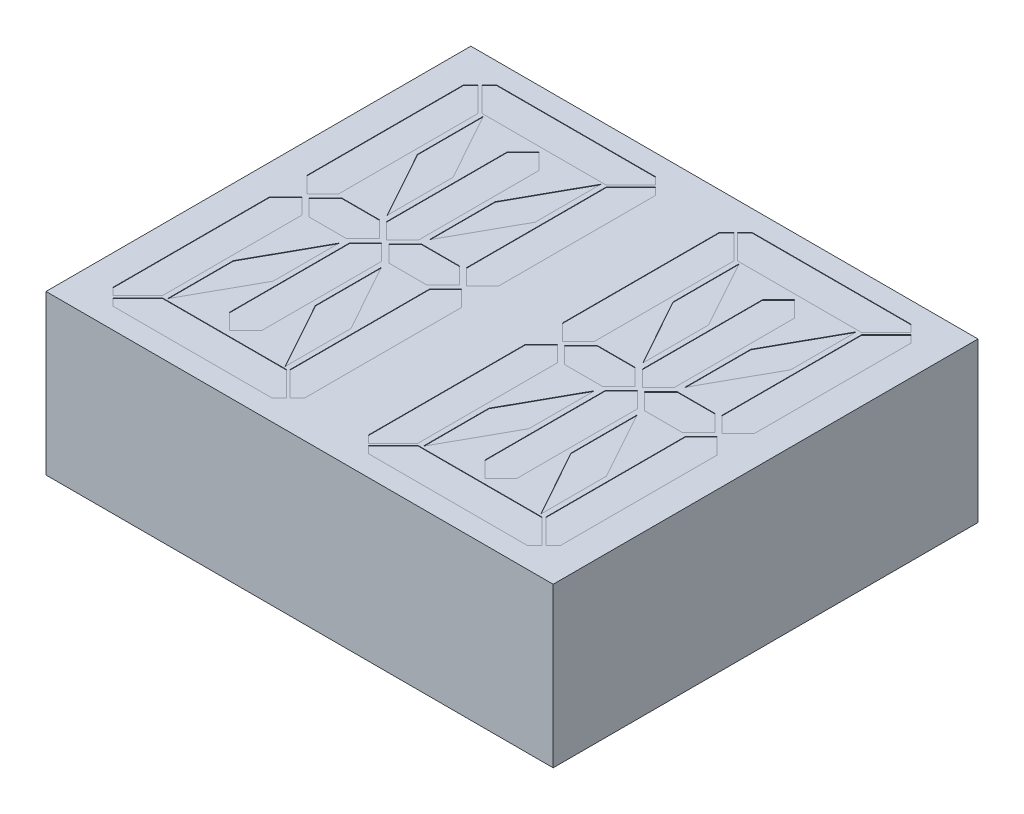
SolidWorks part; units mm, degrees
ref_plane "Front Plane" through (0, 0, 0) normal (0, 0, 1) x (1, 0, 0)
ref_plane "Top Plane" through (0, 0, 0) normal (0, 1, 0) x (1, 0, 0)
ref_plane "Right Plane" through (0, 0, 0) normal (1, 0, 0) x (0, 0, -1)
sketch "Sketch1" plane through (0, 0, 0) normal (0, 1, 0) x (1, 0, 0)
  line L1 (-12.5984, 10.5537) -> (12.5984, 10.5537)
  line L2 (-12.5984, 10.5537) -> (-12.5984, -10.5537)
  line L3 (-12.5984, -10.5537) -> (12.5984, -10.5537)
  line L4 (12.5984, 10.5537) -> (12.5984, -10.5537)
  line L5 (-12.5984, 10.5537) -> (12.5984, -10.5537) construction
  line L6 (-12.5984, -10.5537) -> (12.5984, 10.5537) construction
  point P0 (0, 0)
  dimension "D1" = 25.1968
  dimension "D2" = 21.1074
extrude "Boss-Extrude1" add sketch "Sketch1" along normal blind 7.8994
sketch "Sketch2" plane through (0, 7.8994, 0) normal (0, 1, 0) x (1, 0, 0)
  line L0 (-11.1125, 0.9208) -> (-11.1125, 8.7168)
  line L1 (-11.1125, 8.7168) -> (-10.7533, 9.076)
  line L2 (-10.7533, 9.076) -> (-9.525, 7.8477)
  line L3 (-9.525, 7.8477) -> (-9.525, 0.9208)
  line L4 (-9.525, 0.9208) -> (-10.3188, 0.127)
  line L5 (-10.3188, 0.127) -> (-11.1125, 0.9208)
  line L6 (-9.4352, 7.9375) -> (-10.6635, 9.1658)
  line L7 (-10.6635, 9.1658) -> (-10.3043, 9.525)
  line L8 (-10.3043, 9.525) -> (-2.3957, 9.525)
  line L11 (-3.2648, 7.9375) -> (-9.4352, 7.9375)
  line L12 (-1000, 0) -> (49000, 0) construction
  line L13 (-6.35, 7.6835) -> (-7.1438, 6.8897)
  line L38 (-6.35, -1003.3506) -> (-6.35, 48996.6494) construction
  line L40 (-7.1438, 6.8897) -> (-7.1438, 0.9208)
  line L41 (-7.1438, 0.9208) -> (-6.35, 0.127)
  line L43 (-10.0865, 0) -> (-9.271, 0.8155)
  line L44 (-9.271, 0.8155) -> (-7.3978, 0.8155)
  line L45 (-7.3978, 0.8155) -> (-6.5822, 0)
  line L47 (-9.271, 7.8477) -> (-9.271, 4.5728)
  line L48 (-9.271, 4.5728) -> (-7.3978, 1.1927)
  line L49 (-7.3978, 1.1927) -> (-7.3978, 4.4677)
  line L50 (-7.3978, 4.4677) -> (-9.271, 7.8477)
  line L51 (-5.3023, 4.4677) -> (-3.429, 7.8477)
  line L52 (-5.3023, 1.1927) -> (-5.3023, 4.4677)
  line L53 (-3.429, 4.5728) -> (-5.3023, 1.1927)
  line L54 (-3.429, 7.8477) -> (-3.429, 4.5728)
  line L55 (-5.3023, 0.8155) -> (-6.1178, 0)
  line L56 (-3.429, 0.8155) -> (-5.3023, 0.8155)
  line L57 (-2.6135, 0) -> (-3.429, 0.8155)
  line L58 (-5.5563, 0.9208) -> (-6.35, 0.127)
  line L59 (-5.5563, 6.8897) -> (-5.5563, 0.9208)
  line L60 (-6.35, 7.6835) -> (-5.5563, 6.8897)
  line L63 (-2.0365, 9.1658) -> (-2.3957, 9.525)
  line L64 (-3.2648, 7.9375) -> (-2.0365, 9.1658)
  line L65 (-2.3813, 0.127) -> (-1.5875, 0.9208)
  line L66 (-3.175, 0.9208) -> (-2.3813, 0.127)
  line L67 (-3.175, 7.8477) -> (-3.175, 0.9208)
  line L68 (-1.9467, 9.076) -> (-3.175, 7.8477)
  line L69 (-1.5875, 8.7168) -> (-1.9467, 9.076)
  line L70 (-1.5875, 0.9208) -> (-1.5875, 8.7168)
  line L71 (-1.5875, -0.9208) -> (-1.5875, -8.7168)
  line L72 (-1.5875, -8.7168) -> (-1.9467, -9.076)
  line L73 (-1.9467, -9.076) -> (-3.175, -7.8477)
  line L74 (-3.175, -7.8477) -> (-3.175, -0.9208)
  line L75 (-3.175, -0.9208) -> (-2.3813, -0.127)
  line L76 (-2.3813, -0.127) -> (-1.5875, -0.9208)
  line L77 (-3.2648, -7.9375) -> (-2.0365, -9.1658)
  line L78 (-2.0365, -9.1658) -> (-2.3957, -9.525)
  line L79 (-6.35, -7.6835) -> (-5.5563, -6.8897)
  line L80 (-5.5563, -6.8897) -> (-5.5563, -0.9208)
  line L81 (-5.5563, -0.9208) -> (-6.35, -0.127)
  line L82 (-2.6135, 0) -> (-3.429, -0.8155)
  line L83 (-3.429, -0.8155) -> (-5.3023, -0.8155)
  line L84 (-5.3023, -0.8155) -> (-6.1178, 0)
  line L85 (-3.429, -7.8477) -> (-3.429, -4.5728)
  line L86 (-3.429, -4.5728) -> (-5.3023, -1.1927)
  line L87 (-5.3023, -1.1927) -> (-5.3023, -4.4677)
  line L88 (-5.3023, -4.4677) -> (-3.429, -7.8477)
  line L89 (-7.3978, -4.4677) -> (-9.271, -7.8477)
  line L90 (-7.3978, -1.1927) -> (-7.3978, -4.4677)
  line L91 (-9.271, -4.5728) -> (-7.3978, -1.1927)
  line L92 (-9.271, -7.8477) -> (-9.271, -4.5728)
  line L93 (-7.3978, -0.8155) -> (-6.5822, 0)
  line L94 (-9.271, -0.8155) -> (-7.3978, -0.8155)
  line L95 (-10.0865, 0) -> (-9.271, -0.8155)
  line L96 (-7.1438, -0.9208) -> (-6.35, -0.127)
  line L97 (-7.1438, -6.8897) -> (-7.1438, -0.9208)
  line L98 (-6.35, -7.6835) -> (-7.1438, -6.8897)
  line L99 (-3.2648, -7.9375) -> (-9.4352, -7.9375)
  line L100 (-10.3043, -9.525) -> (-2.3957, -9.525)
  line L101 (-10.6635, -9.1658) -> (-10.3043, -9.525)
  line L102 (-9.4352, -7.9375) -> (-10.6635, -9.1658)
  line L103 (-10.3188, -0.127) -> (-11.1125, -0.9208)
  line L104 (-9.525, -0.9208) -> (-10.3188, -0.127)
  line L105 (-9.525, -7.8477) -> (-9.525, -0.9208)
  line L106 (-10.7533, -9.076) -> (-9.525, -7.8477)
  line L107 (-11.1125, -8.7168) -> (-10.7533, -9.076)
  line L108 (-11.1125, -0.9208) -> (-11.1125, -8.7168)
  point P15 (-6.6465, 0)
  point P26 (0, 0)
  point P27 (0, 0)
  point P28 (0, 0)
  point P29 (-6.35, 0)
  point P30 (-7.0927, 0)
  point P31 (-6.2145, 0.508)
  point P32 (-6.4969, 0)
  point P33 (-10.1669, 0)
  point P34 (0, 0)
  point P35 (0, 0)
  point P50 (-6.35, 7.9375)
  point P51 (-6.35, 9.525)
  point P92 (0, 0)
  point P93 (-6.6174, 0)
  point P96 (-6.35, -9.525)
  point P97 (-6.35, -7.9375)
  dimension "D2" = 6.35
  dimension "D3" = 1.5875
  dimension "D4" = 0.127
  dimension "D5" = 0.508
  dimension "D6" = 135
  dimension "D7" = 9.525
  dimension "D8" = 19.05
  dimension "D9" = 0.254
  dimension "D10" = 0.254
  dimension "D11" = 0.254
  dimension "D12" = 0.254
  dimension "D13" = 1.5875
  dimension "D14" = 0.127
  dimension "D15" = 0.254
extrude "Cut-Extrude1" cut sketch "Sketch2" against normal blind 0.0254
mirror "Mirror1" about plane through (0, 0, 0) normal (1, 0, 0) of "Cut-Extrude1"
